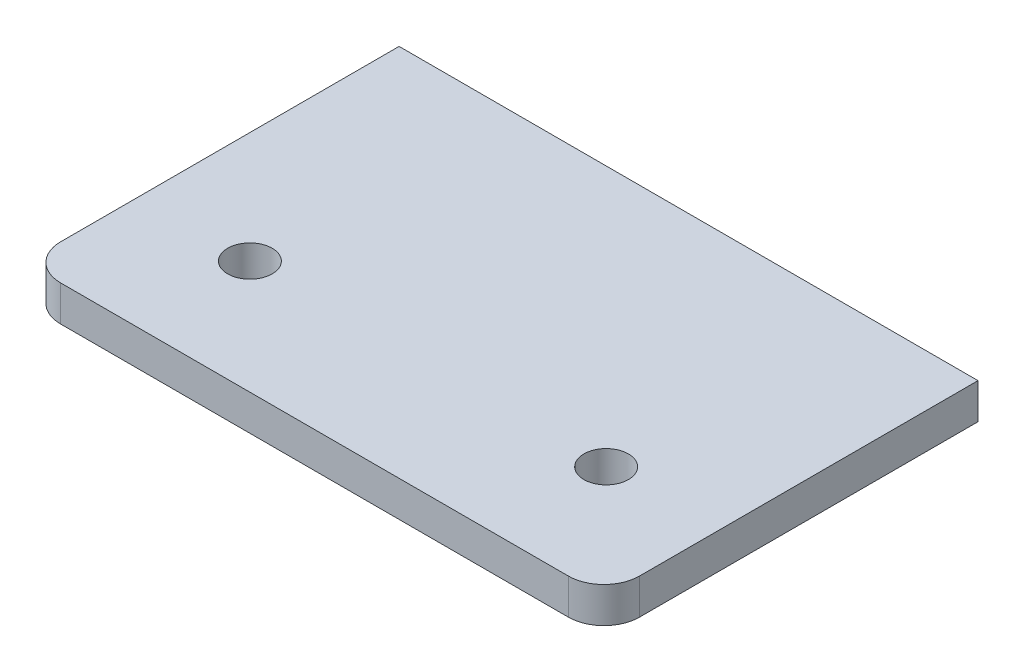
SolidWorks part; units mm, degrees
ref_plane "Front Plane" through (0, 0, 0) normal (0, 0, 1) x (1, 0, 0)
ref_plane "Top Plane" through (0, 0, 0) normal (0, 1, 0) x (1, 0, 0)
ref_plane "Right Plane" through (0, 0, 0) normal (1, 0, 0) x (0, 0, -1)
sketch "Sketch1" plane through (0, 0, 0) normal (0, 1, 0) x (1, 0, 0)
  line L1 (4, 0) -> (61, 0)
  line L2 (0, 4) -> (0, 42)
  line L3 (0, 42) -> (65, 42)
  line L4 (65, 4) -> (65, 42)
  arc A0 (65, 4) -> (61, 0) centre (61, 4) cw
  arc A1 (0, 4) -> (4, 0) centre (4, 4) ccw
  circle A2 centre (12.5, 12.75) radius 2.5
  circle A3 centre (52.5, 12.75) radius 2.5
  point P7 (65, 0)
  point P10 (0, 0)
  dimension "D3" = 4
  dimension "D8" = 5
  dimension "D9" = 5
  dimension "D1" = 42
  dimension "D2" = 65
  dimension "D4" = 12.75
  dimension "D5" = 40
  dimension "D6" = 12.75
  dimension "D7" = 12.5
extrude "Boss-Extrude1" add sketch "Sketch1" along normal blind 4
